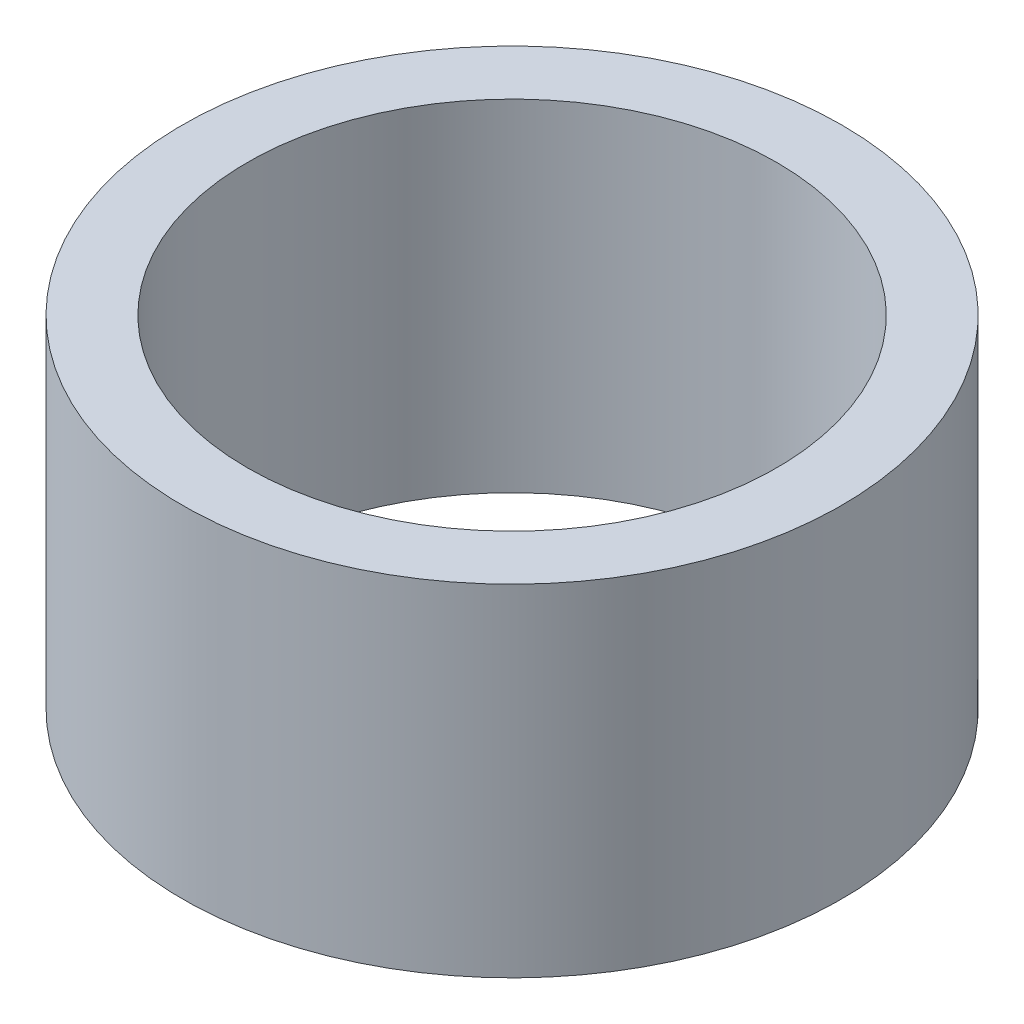
SolidWorks part; units mm, degrees
ref_plane "Front Plane" through (0, 0, 0) normal (0, 0, 1) x (1, 0, 0)
ref_plane "Top Plane" through (0, 0, 0) normal (0, 1, 0) x (1, 0, 0)
ref_plane "Right Plane" through (0, 0, 0) normal (1, 0, 0) x (0, 0, -1)
sketch "Sketch1" plane through (0, 0, 0) normal (0, 1, 0) x (1, 0, 0)
  circle A0 centre (0, 0) radius 8.15
  circle A1 centre (0, 0) radius 10.15
  dimension "D1" = 16.3
  dimension "D2" = 2
extrude "Boss-Extrude1" add sketch "Sketch1" along normal blind 10.5
